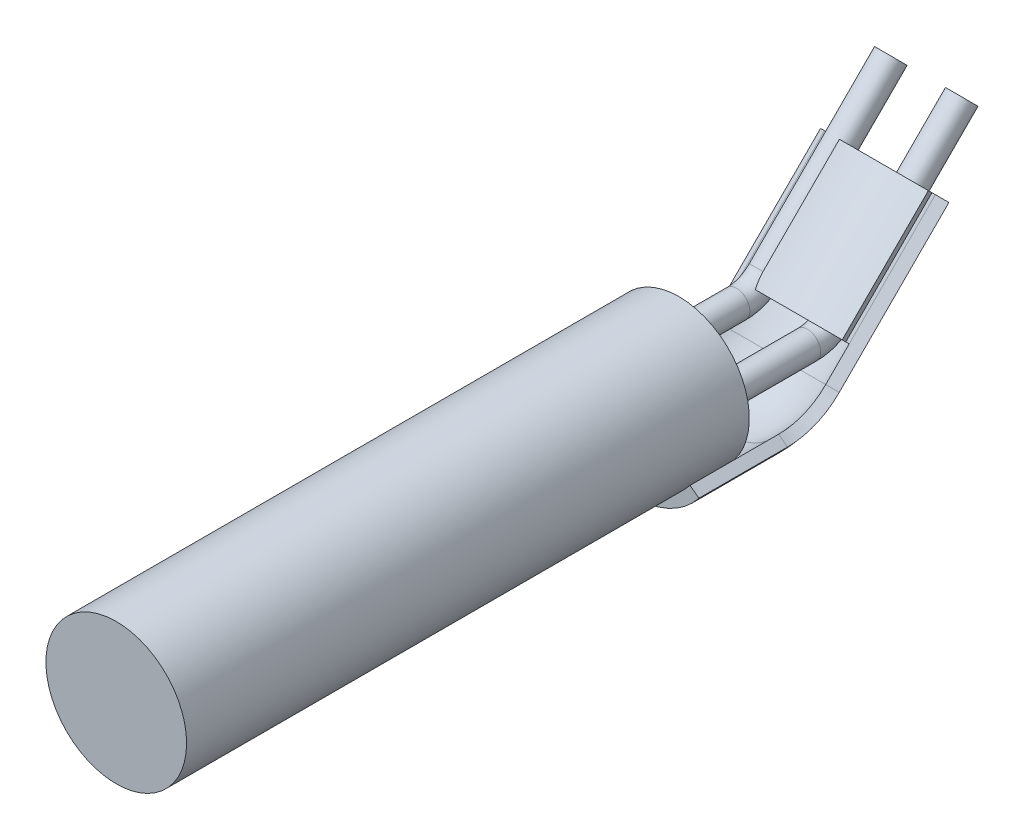
SolidWorks part; units mm, degrees
ref_plane "Front Plane" through (0, 0, 0) normal (0, 0, 1) x (1, 0, 0)
ref_plane "Top Plane" through (0, 0, 0) normal (0, 1, 0) x (1, 0, 0)
ref_plane "Right Plane" through (0, 0, 0) normal (1, 0, 0) x (0, 0, -1)
sketch "Sketch1" plane through (0, 0, 0) normal (0, 0, 1) x (1, 0, 0)
  circle A0 centre (0, 0) radius 3.175
  dimension "D1" = 6.35
extrude "Boss-Extrude1" add sketch "Sketch1" along normal blind 25.4
sketch "Sketch2" plane through (0, 0, 0) normal (0, 0, -1) x (-1, 0, 0)
  line L0 (55, 0) -> (-55, 0) construction
  line L1 (0, 0) -> (0, 3.818) construction
  line L2 (0, 55) -> (0, -55) construction
  line L3 (0, 0) -> (5.2921, 0) construction
  circle A0 centre (-1.6, 0) radius 0.6
  circle A1 centre (1.6, 0) radius 0.6
  dimension "D2" = 1.2
  dimension "D1" = 3.2
extrude "Boss-Extrude2" add sketch "Sketch2" along normal blind 0.5
sketch "Sketch3" plane through (0, 0, 0) normal (0, 0, -1) x (-1, 0, 0)
  line L0 (-2.5029, -1.9535) -> (-2.8971, -2.2611)
  line L1 (0, 0) -> (0, -3.675) construction
  line L2 (2.5029, -1.9535) -> (2.8971, -2.2611)
  arc A0 (-2.5029, -1.9535) -> (2.5029, -1.9535) centre (0, 0) ccw
  circle A1 centre (0, 0) radius 3.175 construction
  arc A2 (-2.8971, -2.2611) -> (2.8971, -2.2611) centre (0, 0) ccw
  arc A3 (-2.7, -2.1073) -> (2.7, -2.1073) centre (0, 0) ccw construction
  dimension "D1" = 0.5
  dimension "D2" = 5.4
extrude "Boss-Extrude4" add sketch "Sketch3" against normal blind 2
sketch "Sketch4" plane through (0, 0, 0) normal (1, 0, 0) x (0, 0, -1)
  line L0 (-2, -1.9535) -> (0, -1.9535) construction
  line L1 (0, -3.675) -> (0, -2.2611) construction
  line L2 (0, -1.9535) -> (2, -1.9535)
  line L3 (4.1213, -1.0748) -> (9.0711, 3.875)
  arc A0 (2, -1.9535) -> (4.1213, -1.0748) centre (2, 1.0465) ccw
  point P3 (0, -1.9535)
  dimension "D4" = 3
  dimension "D1" = 2
  dimension "D2" = 7
  dimension "D3" = 45
sketch "Sketch5" plane through (0, 0, 0) normal (0, 0, -1) x (-1, 0, 0)
  line L0 (2.8971, -2.2611) -> (2.5029, -1.9535) construction
  line L1 (-2.8971, -2.2611) -> (-2.5029, -1.9535)
  line L2 (2.5029, -1.9535) -> (2.8971, -2.2611)
  arc A0 (-2.8971, -2.2611) -> (2.8971, -2.2611) centre (0, 0) ccw
  arc A1 (-2.5029, -1.9535) -> (2.5029, -1.9535) centre (0, 0) ccw
  arc A2 (2.5029, -1.9535) -> (-2.5029, -1.9535) centre (0, 0) ccw construction
sweep "Sweep2" add profiles "Sketch5" path "Sketch4"
sketch "Sketch6" plane through (0, 0, -0.5) normal (0, 0, -1) x (-1, 0, 0)
  circle A0 centre (-1.6, 0) radius 0.6 construction
  circle A1 centre (1.6, 0) radius 0.6 construction
  circle A2 centre (-1.6, 0) radius 0.6
  circle A3 centre (1.6, 0) radius 0.6
sketch "Sketch7" plane through (0, 0, 0) normal (1, 0, 0) x (0, 0, -1)
  line L0 (0.5, 0.6) -> (4.2, 0.6)
  line L3 (5.0839, 0.9661) -> (10.7407, 6.623)
  line L4 (4.1213, -1.0748) -> (9.0711, 3.875) construction
  arc A0 (4.2, 0.6) -> (5.0839, 0.9661) centre (4.2, 1.85) ccw
  dimension "D2" = 1.25
  dimension "D1" = 3.7
  dimension "D3" = 8
sweep "Sweep3" add profiles "Sketch6" path "Sketch7"
sketch "Sketch8" plane through (0, 6.473, -6.473) normal (0, 0.7071, -0.7071) x (1, 0, 0)
  line L0 (2.7811, 2.8355) -> (2.6107, 3.3055)
  line L1 (-1.6451, 4.2371) -> (-1.2435, 4.535)
  line L2 (-2.8971, 3.9818) -> (-2.5029, 3.6742)
  line L3 (2.5029, 3.6742) -> (2.8971, 3.9818)
  line L4 (-2.8971, 3.9818) -> (-2.5029, 3.6742)
  line L5 (2.5029, 3.6742) -> (2.8971, 3.9818)
  arc A0 (2.5029, 3.6742) -> (-1.6451, 4.2371) centre (0.7036, 5.9797) cw
  arc A1 (-2.5029, 3.6742) -> (2.7811, 2.8355) centre (0.8972, 8.0306) ccw
  arc A2 (2.8971, 3.9818) -> (-2.8971, 3.9818) centre (0, 1.7207) ccw
  arc A3 (2.5029, 3.6742) -> (-2.5029, 3.6742) centre (0, 1.7207) ccw
  arc A4 (2.8971, 3.9818) -> (-2.8971, 3.9818) centre (0, 1.7207) ccw
  arc A5 (-1.2435, 4.535) -> (2.1638, 4.0442) centre (0.7036, 5.9797) ccw
  arc A6 (2.5029, 3.6742) -> (-2.5029, 3.6742) centre (0, 1.7207) ccw construction
  arc A7 (2.6107, 3.3055) -> (-2.1639, 4.0441) centre (0.8972, 8.0306) cw
  arc A8 (2.1638, 4.0442) -> (-2.1639, 4.0441) centre (0, 1.7207) ccw
  dimension "D1" = 0
extrude "Boss-Extrude5" add sketch "Sketch8" against normal blind 5.5
